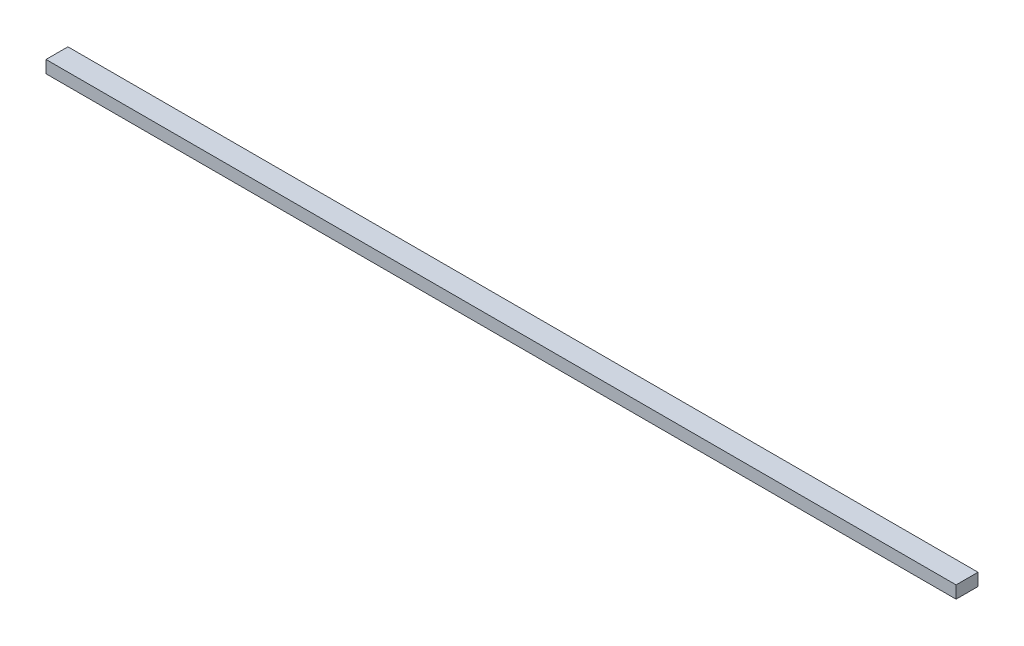
SolidWorks part; units mm, degrees
ref_plane "Front Plane" through (0, 0, 0) normal (0, 0, 1) x (1, 0, 0)
ref_plane "Top Plane" through (0, 0, 0) normal (0, 1, 0) x (1, 0, 0)
ref_plane "Right Plane" through (0, 0, 0) normal (1, 0, 0) x (0, 0, -1)
sketch "Sketch1" plane through (0, 0, 0) normal (0, 1, 0) x (1, 0, 0)
  line L1 (-110, 2.65) -> (110, 2.65)
  line L2 (-110, 2.65) -> (-110, -2.65)
  line L3 (-110, -2.65) -> (110, -2.65)
  line L4 (110, 2.65) -> (110, -2.65)
  line L5 (-110, 2.65) -> (110, -2.65) construction
  line L6 (-110, -2.65) -> (110, 2.65) construction
  point P0 (0, 0)
  dimension "D1" = 5.3
  dimension "D2" = 220
extrude "Boss-Extrude1" add sketch "Sketch1" along normal blind 3
